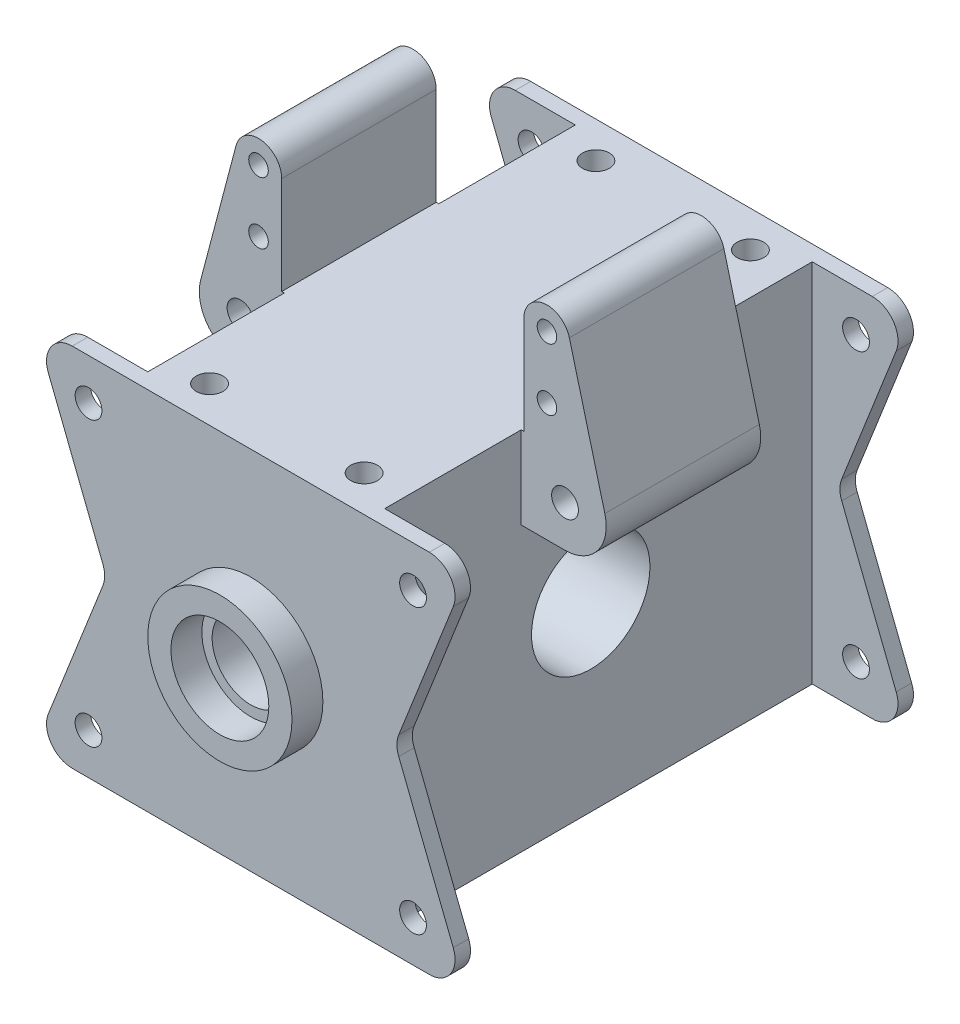
SolidWorks part; units mm, degrees
material "7050-T73510"
ref_plane "前视基准面" through (0, 0, 0) normal (0, 0, 1) x (1, 0, 0)
ref_plane "上视基准面" through (0, 0, 0) normal (0, 1, 0) x (1, 0, 0)
ref_plane "右视基准面" through (0, 0, 0) normal (1, 0, 0) x (0, 0, -1)
sketch "草图1" plane through (0, 0, 0) normal (0, 1, 0) x (1, 0, 0)
  line L1 (-23, -44.5) -> (23, -44.5)
  line L2 (-23, -44.5) -> (-23, 44.5)
  line L3 (-23, 44.5) -> (23, 44.5)
  line L4 (23, -44.5) -> (23, 44.5)
  line L5 (-23, -44.5) -> (23, 44.5) construction
  line L6 (-23, 44.5) -> (23, -44.5) construction
  point P0 (0, 0)
  dimension "D1" = 46
  dimension "D2" = 89
extrude "凸台-拉伸1" add sketch "草图1" along normal mid plane 71
sketch "草图3" plane through (0, 0, 44.5) normal (0, 0, 1) x (1, 0, 0)
  line L0 (0, 44.618) -> (0, -47.7189) construction
  line L1 (23, 35.5) -> (34.6534, 35.5)
  line L2 (-31.5, -27.5) -> (31.5, -27.5) construction
  line L3 (-31.5, -27.5) -> (-31.5, 27.5) construction
  line L4 (-31.5, 27.5) -> (31.5, 27.5) construction
  line L5 (31.5, -27.5) -> (31.5, 27.5) construction
  line L6 (-31.5, -27.5) -> (31.5, 27.5) construction
  line L7 (-31.5, 27.5) -> (31.5, -27.5) construction
  line L8 (39.3048, 28.6657) -> (28.7234, 1.8343)
  line L9 (28, 0) -> (23, 0) construction
  line L10 (23, 35.5) -> (23, -35.5) construction
  line L11 (23, -35.5) -> (23, 35.5)
  line L12 (39.3048, -28.6657) -> (28.7234, -1.8343)
  line L13 (23, -35.5) -> (34.6534, -35.5)
  line L14 (-23, -35.5) -> (-23, 35.5)
  line L15 (-39.3048, -28.6657) -> (-28.7234, -1.8343)
  line L16 (-39.3048, 28.6657) -> (-28.7234, 1.8343)
  line L17 (-23, 35.5) -> (-34.6534, 35.5)
  line L18 (-34.6534, -35.5) -> (-23, -35.5)
  circle A1 centre (31.5, 27.5) radius 2.6
  circle A2 centre (31.5, -27.5) radius 2.6
  circle A3 centre (-31.5, -27.5) radius 2.6
  circle A4 centre (-31.5, 27.5) radius 2.6
  arc A5 (-39.3048, 28.6657) -> (-34.6534, 35.5) centre (-34.6534, 30.5) cw
  arc A6 (-28.7234, -1.8343) -> (-28.7234, 1.8343) centre (-33.3748, 0) ccw
  arc A7 (-39.3048, -28.6657) -> (-34.6534, -35.5) centre (-34.6534, -30.5) ccw
  arc A8 (39.3048, -28.6657) -> (34.6534, -35.5) centre (34.6534, -30.5) cw
  arc A9 (28.7234, 1.8343) -> (28.7234, -1.8343) centre (33.3748, 0) ccw
  arc A10 (34.6534, 35.5) -> (39.3048, 28.6657) centre (34.6534, 30.5) cw
  point P3 (0, 0)
  point P28 (-42, 35.5)
  point P31 (-28, 0)
  point P34 (-42, -35.5)
  point P37 (42, -35.5)
  point P43 (42, 35.5)
  dimension "D3" = 5.2
  dimension "D6" = 5
  dimension "D1" = 63
  dimension "D2" = 55
  dimension "D4" = 19
  dimension "D5" = 5
extrude "凸台-拉伸2" add sketch "草图3" against normal blind 3
sketch "草图4" plane through (0, 0, -44.5) normal (0, 0, -1) x (-1, 0, 0)
  line L5 (39.3048, -28.6657) -> (28.7234, -1.8343)
  line L6 (28.7234, 1.8343) -> (39.3048, 28.6657)
  line L7 (34.6534, 35.5) -> (23, 35.5)
  line L8 (23, 35.5) -> (23, -35.5)
  line L9 (23, -35.5) -> (34.6534, -35.5)
  line L10 (39.3048, -28.6657) -> (28.7234, -1.8343)
  line L11 (28.7234, 1.8343) -> (39.3048, 28.6657)
  line L12 (34.6534, 35.5) -> (23, 35.5)
  line L13 (23, 35.5) -> (23, -35.5)
  line L14 (23, -35.5) -> (34.6534, -35.5)
  line L15 (-23, 35.5) -> (-34.6534, 35.5)
  line L16 (-23, -35.5) -> (-23, 35.5)
  line L17 (-34.6534, -35.5) -> (-23, -35.5)
  line L18 (-28.7234, -1.8343) -> (-39.3048, -28.6657)
  line L19 (-39.3048, 28.6657) -> (-28.7234, 1.8343)
  line L20 (-23, 35.5) -> (-34.6534, 35.5)
  line L21 (-23, -35.5) -> (-23, 35.5)
  line L22 (-34.6534, -35.5) -> (-23, -35.5)
  line L23 (-28.7234, -1.8343) -> (-39.3048, -28.6657)
  line L24 (-39.3048, 28.6657) -> (-28.7234, 1.8343)
  circle A1 centre (31.5, 27.5) radius 2.6
  circle A2 centre (31.5, 27.5) radius 2.6
  circle A3 centre (31.5, -27.5) radius 2.6
  circle A4 centre (31.5, -27.5) radius 2.6
  circle A5 centre (-31.5, -27.5) radius 2.6
  circle A6 centre (-31.5, -27.5) radius 2.6
  circle A7 centre (-31.5, 27.5) radius 2.6
  circle A8 centre (-31.5, 27.5) radius 2.6
  arc A11 (28.7234, 1.8343) -> (28.7234, -1.8343) centre (33.3748, 0) ccw
  arc A12 (39.3048, 28.6657) -> (34.6534, 35.5) centre (34.6534, 30.5) ccw
  arc A13 (34.6534, -35.5) -> (39.3048, -28.6657) centre (34.6534, -30.5) ccw
  arc A14 (28.7234, 1.8343) -> (28.7234, -1.8343) centre (33.3748, 0) ccw
  arc A15 (39.3048, 28.6657) -> (34.6534, 35.5) centre (34.6534, 30.5) ccw
  arc A16 (34.6534, -35.5) -> (39.3048, -28.6657) centre (34.6534, -30.5) ccw
  arc A17 (-39.3048, -28.6657) -> (-34.6534, -35.5) centre (-34.6534, -30.5) ccw
  arc A18 (-28.7234, -1.8343) -> (-28.7234, 1.8343) centre (-33.3748, 0) ccw
  arc A19 (-34.6534, 35.5) -> (-39.3048, 28.6657) centre (-34.6534, 30.5) ccw
  arc A20 (-39.3048, -28.6657) -> (-34.6534, -35.5) centre (-34.6534, -30.5) ccw
  arc A21 (-28.7234, -1.8343) -> (-28.7234, 1.8343) centre (-33.3748, 0) ccw
  arc A22 (-34.6534, 35.5) -> (-39.3048, 28.6657) centre (-34.6534, 30.5) ccw
  dimension "D1" = 0
  dimension "D2" = 0
  dimension "D3" = 0
  dimension "D4" = 0
  dimension "D5" = 0
  dimension "D6" = 0
extrude "凸台-拉伸3" add sketch "草图4" against normal blind 3
sketch "草图5" plane through (0, 0, 44.5) normal (0, 0, 1) x (1, 0, 0)
  circle A0 centre (0, 0) radius 14
  dimension "D1" = 28
extrude "凸台-拉伸4" add sketch "草图5" along normal blind 6
sketch "草图6" plane through (23, 0, 0) normal (1, 0, 0) x (0, 0, -1)
  line L0 (44.5, -1.8343) -> (44.5, 1.8343) construction
  circle A0 centre (-1.5, 0) radius 11.5
  dimension "D2" = 23
  dimension "D1" = 46
extrude "切除-拉伸1" cut sketch "草图6" against normal through all
sketch "草图7" plane through (0, 0, 0) normal (0, 0, 1) x (1, 0, 0)
  line L0 (23, 19.5) -> (23, 35.5)
  line L1 (-39.3048, 28.6657) -> (-28.7234, 1.8343) construction
  line L3 (23, 35.5) -> (31.5, 35.5)
  line L4 (-39.3048, 28.6657) -> (-28.7234, 1.8343) construction
  line L5 (-34.6534, 35.5) -> (-23, 35.5) construction
  line L6 (23, 35.5) -> (23, -35.5) construction
  line L7 (23, 19.5) -> (23, -35.5) construction
  line L8 (-23, 35.5) -> (-23, -35.5) construction
  line L9 (-23, 35.5) -> (-23, -35.5) construction
  line L10 (23, 19.5) -> (31.5, 19.5)
  arc A1 (-34.6534, 35.5) -> (-39.3048, 28.6657) centre (-34.6534, 30.5) ccw construction
  arc A2 (31.5, 19.5) -> (31.5, 35.5) centre (31.5, 27.5) ccw
  arc A3 (-34.6534, 35.5) -> (-39.3048, 28.6657) centre (-34.6534, 30.5) ccw construction
  circle A4 centre (-31.5, 27.5) radius 2.6 construction
  circle A5 centre (-31.5, 27.5) radius 2.6 construction
  circle A6 centre (31.5, 27.5) radius 2.6 construction
  circle A7 centre (31.5, 27.5) radius 2.6
  dimension "D1" = 16
extrude "凸台-拉伸5" add sketch "草图7" along normal mid plane 30
mirror "镜向1" about plane through (0, 0, 0) normal (1, 0, 0) of "凸台-拉伸5"
sketch "草图8" plane through (0, 0, 0) normal (0, 0, 1) x (1, 0, 0)
  line L0 (32.3513, 55.6474) -> (39.2356, 29.5398)
  line L1 (0, 0) -> (0, 72.2973) construction
  line L2 (-34.6534, 35.5) -> (34.6534, 35.5) construction
  line L3 (23.5, 54.5) -> (23.5, 35.5)
  line L4 (23.5, 35.5) -> (31.5, 35.5)
  circle A0 centre (28, 54.5) radius 1.9
  circle A1 centre (28, 42.5) radius 1.9
  circle A2 centre (28, 54.5) radius 4.5
  arc A3 (31.5, 19.5) -> (31.5, 35.5) centre (31.5, 27.5) ccw construction
  arc A4 (31.5, 19.5) -> (31.5, 35.5) centre (31.5, 27.5) ccw
  dimension "D2" = 9
  dimension "D3" = 3.8
  dimension "D4" = 12
  dimension "D5" = 7
  dimension "D1" = 28
extrude "凸台-拉伸6" add sketch "草图8" along normal mid plane 30 contours A4 L0 A2 L3 L4 A1 | A2 A0
mirror "镜向2" about plane through (0, 0, 0) normal (1, 0, 0) of "凸台-拉伸6", "凸台-拉伸5"
sketch "草图9" plane through (0, -35.5, 0) normal (0, -1, 0) x (1, 0, 0)
  line L1 (-15, -37.5) -> (15, -37.5) construction
  line L2 (-15, -37.5) -> (-15, 37.5) construction
  line L3 (-15, 37.5) -> (15, 37.5) construction
  line L4 (15, -37.5) -> (15, 37.5) construction
  line L5 (-15, -37.5) -> (15, 37.5) construction
  line L6 (-15, 37.5) -> (15, -37.5) construction
  circle A0 centre (15, -37.5) radius 2.6
  circle A1 centre (-15, -37.5) radius 2.6
  circle A2 centre (-15, 37.5) radius 2.6
  circle A3 centre (15, 37.5) radius 2.6
  point P0 (0, 0)
  dimension "D3" = 5.2
  dimension "D1" = 30
  dimension "D2" = 75
extrude "切除-拉伸2" cut sketch "草图9" against normal through all
sketch "草图10" plane through (0, 0, 50.5) normal (0, 0, 1) x (1, 0, 0)
  circle A0 centre (0, 0) radius 9.5
  dimension "D1" = 19
extrude "切除-拉伸3" cut sketch "草图10" against normal blind 6
sketch "草图11" plane through (0, 0, 44.5) normal (0, 0, 1) x (1, 0, 0)
  circle A0 centre (0, 0) radius 7.5
  dimension "D1" = 15
extrude "切除-拉伸4" cut sketch "草图11" against normal blind 6
sketch "草图12" plane through (0, 0, 38.5) normal (0, 0, 1) x (1, 0, 0)
  circle A0 centre (0, 0) radius 9.5
  dimension "D1" = 19
extrude "切除-拉伸5" cut sketch "草图12" against normal blind 6
sketch "草图14" plane through (0, 0, 50.5) normal (0, 0, 1) x (1, 0, 0)
  line L1 (107.3074, -80.5368) -> (0, -80.5368)
  line L2 (107.3074, -80.5368) -> (107.3074, 80.5368)
  line L3 (107.3074, 80.5368) -> (0, 80.5368)
  line L4 (0, -80.5368) -> (0, 80.5368)
  line L5 (107.3074, -80.5368) -> (0, 80.5368) construction
  line L6 (107.3074, 80.5368) -> (0, -80.5368) construction
  point P0 (53.6537, 0)
